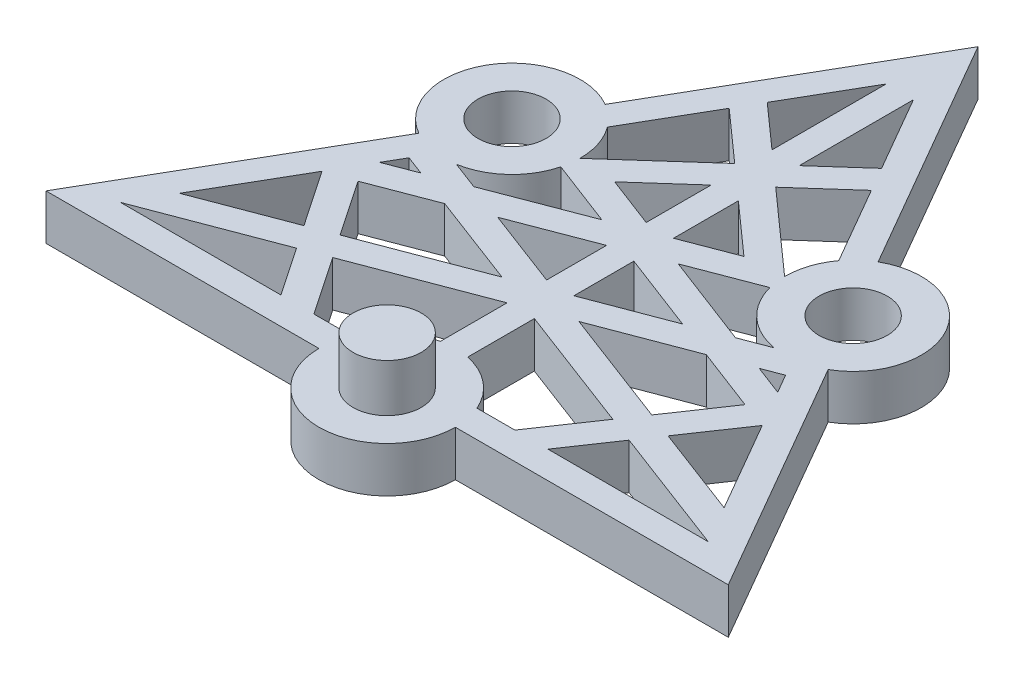
SolidWorks part; units mm, degrees
ref_plane "Front Plane" through (0, 0, 0) normal (0, 0, 1) x (1, 0, 0)
ref_plane "Top Plane" through (0, 0, 0) normal (0, 1, 0) x (1, 0, 0)
ref_plane "Right Plane" through (0, 0, 0) normal (1, 0, 0) x (0, 0, -1)
sketch "Sketch1" plane through (0, 0, 0) normal (0, 1, 0) x (1, 0, 0)
  line L0 (-2.187, 14.7527) -> (-17.187, -11.228)
  line L1 (-17.187, -11.228) -> (12.813, -11.228)
  line L2 (12.813, -11.228) -> (-2.187, 14.7527)
  dimension "D1" = 30
extrude "Extrude-Thin1" add sketch "Sketch1" along normal blind 2 thin thin type one direction reverse wall 1.2
sketch "Sketch2" plane through (0, 0, 0) normal (0, 1, 0) x (1, 0, 0)
  line L3 (12.813, -11.228) -> (-2.187, 14.7527) construction
  line L4 (-17.187, -11.228) -> (12.813, -11.228) construction
  line L5 (-2.187, 14.7527) -> (-17.187, -11.228) construction
  circle A0 centre (-9.687, 1.7624) radius 3
  circle A1 centre (5.313, 1.7624) radius 3
  circle A2 centre (-2.187, -11.228) radius 3
  point P6 (8.3878, 3.3379)
  point P9 (5.313, 1.7624)
  point P12 (-2.187, -11.228)
  point P15 (-9.687, 1.7624)
  point P16 (0, 0)
  dimension "D1" = 6
extrude "Boss-Extrude1" add sketch "Sketch2" along normal up to surface (2 mm away) up to face at (-2.187, 2, 2.5678)
sketch "Sketch3" plane through (0, 0, 0) normal (0, 1, 0) x (1, 0, 0)
  circle A0 centre (-9.687, 1.7624) radius 1.5
  circle A1 centre (5.313, 1.7624) radius 1.5
  dimension "D1" = 3
extrude "Cut-Extrude1" cut sketch "Sketch3" along normal through all
sketch "Sketch4" plane through (0, 2, 0) normal (0, 1, 0) x (1, 0, 0)
  circle A0 centre (-2.187, -11.228) radius 1.5
  point P2 (0, 0)
extrude "Boss-Extrude2" add sketch "Sketch4" along normal blind 2.1
sketch "Sketch5" plane through (0, 0, 0) normal (0, 1, 0) x (1, 0, 0)
  line L0 (-5.3882, 8.6118) -> (2.9261, 1.2029)
  line L1 (2.9261, 1.2029) -> (-10.6966, -4)
  line L3 (-10.6966, -4) -> (-6.4433, -10.2665)
  point P2 (2.9261, 1.2029)
  point P4 (-10.6966, -4)
  point P7 (0, 0)
  point P8 (-6.4433, -10.2665)
  point P9 (0, 0)
  point P10 (0, 0)
extrude "Extrude-Thin2" add sketch "Sketch5" along normal up to surface (2 mm away) thin
sketch "Sketch6" plane through (0, 0, 0) normal (0, 1, 0) x (1, 0, 0)
  line L0 (-15.1086, -10.028) -> (6.4832, -1.8388)
  point P3 (6.4832, -1.8388)
extrude "Extrude-Thin3" add sketch "Sketch6" along normal up to surface (2 mm away) thin thin type one direction reverse wall 1.2
ref_plane "Plane1" through (-2.187, 0, 0) normal (1, 0, 0) x (0, 0, -1)
mirror "Mirror1" about plane through (-2.187, 0, 0) normal (1, 0, 0) of "Extrude-Thin3", "Extrude-Thin2"
sketch "Sketch7" plane through (0, 0, 0) normal (0, 1, 0) x (1, 0, 0)
  line L0 (-2.187, -11.228) -> (-2.187, 12.7479)
extrude "Extrude-Thin4" add sketch "Sketch7" along normal up to surface (2 mm away) thin thin type mid plane wall 1.2
